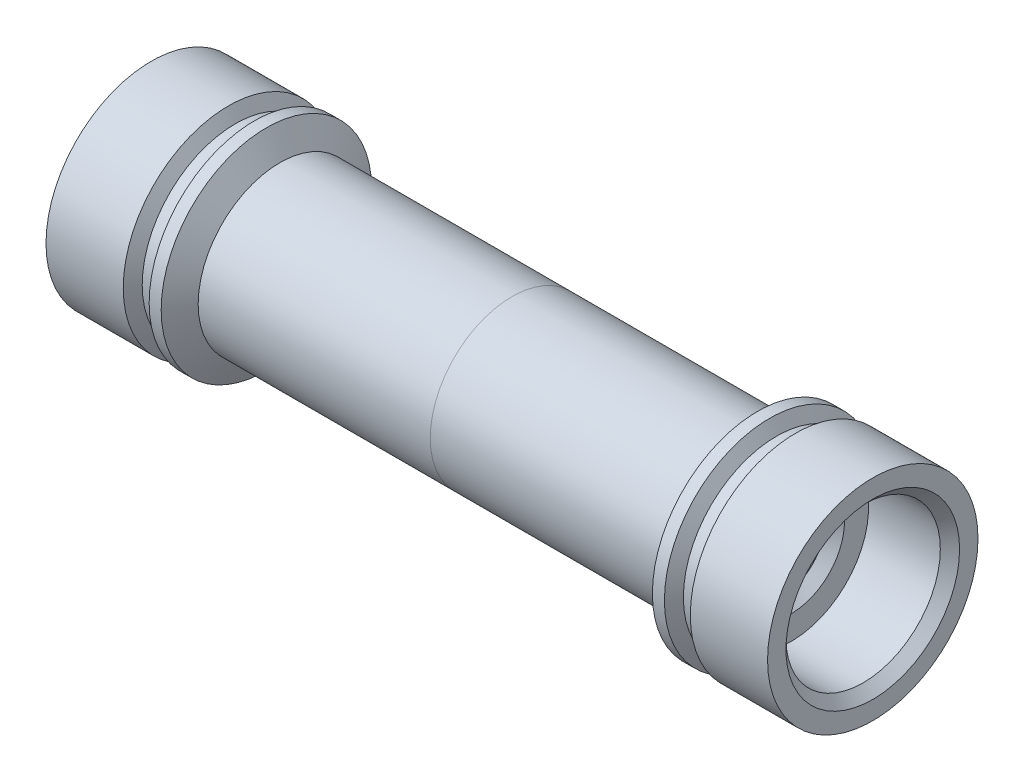
SolidWorks part; units mm, degrees
ref_plane "Front Plane" through (0, 0, 0) normal (0, 0, 1) x (1, 0, 0)
ref_plane "Top Plane" through (0, 0, 0) normal (0, 1, 0) x (1, 0, 0)
ref_plane "Right Plane" through (0, 0, 0) normal (1, 0, 0) x (0, 0, -1)
sketch "Sketch2" plane through (0, 0, 0) normal (0, 0, 1) x (1, 0, 0)
  line L0 (0, 0) -> (0, 28.4375) construction
  line L1 (-19.05, 4.075) -> (-14.75, 4.075) construction
  line L2 (-19.05, 4.075) -> (-19.05, -4.075) construction
  line L3 (-19.05, -4.075) -> (-14.75, -4.075) construction
  line L4 (-14.75, 4.075) -> (-14.75, -4.075) construction
  line L5 (-19.05, 4.075) -> (-14.75, -4.075) construction
  line L6 (-19.05, -4.075) -> (-14.75, 4.075) construction
  line L7 (14.75, 4.5) -> (48.8332, 4.5) construction
  line L8 (14.75, 4.5) -> (14.75, -4.5) construction
  line L9 (14.75, -4.5) -> (48.8332, -4.5) construction
  line L10 (48.8332, 4.5) -> (48.8332, -4.5) construction
  line L11 (14.75, 4.5) -> (48.8332, -4.5) construction
  line L12 (14.75, -4.5) -> (48.8332, 4.5) construction
  line L13 (-19.05, 0) -> (48.8332, 0) construction
  line L14 (-19.05, 5.5562) -> (-14.9716, 5.5562)
  line L21 (-12.2535, 4.318) -> (0, 4.318)
  line L22 (-19.05, 5.5562) -> (-19.05, 4.075)
  line L23 (-19.05, 4.075) -> (-14.75, 4.075)
  line L24 (-14.75, 4.075) -> (-14.75, 0)
  line L25 (-14.75, 0) -> (0, 0)
  line L26 (0, 0) -> (0, 4.318)
  line L27 (-33.5594, -5.5562) -> (-33.5594, 5.5562) construction
  line L28 (-14.9716, 5.5562) -> (-14.605, 4.9212)
  line L29 (-14.605, 4.9212) -> (-13.97, 4.9212)
  line L30 (-19.05, 5.5562) -> (19.05, 5.5562) construction
  line L31 (0, 1.625) -> (-6.5, 1.625)
  line L32 (-6.5, 1.625) -> (-8.125, 0)
  line L33 (-6.5, 1.625) -> (-6.5, -1.625) construction
  line L34 (-6.5, 1.625) -> (6.5, 1.625) construction
  line L35 (-14.75, 1.905) -> (-9.098, 1.905)
  line L36 (-9.098, 1.905) -> (-9.098, 0)
  line L37 (-14.75, 2.805) -> (-14.242, 2.297)
  line L38 (-9.098, 1.905) -> (-22.098, 1.905) construction
  line L39 (-9.098, 1.905) -> (-9.098, -1.905) construction
  line L40 (-9.098, -1.905) -> (-22.098, -1.905) construction
  line L41 (-22.098, 1.905) -> (-22.098, -1.905) construction
  line L42 (-14.242, 2.297) -> (-14.242, 0)
  line L46 (-13.97, 4.9212) -> (-13.6034, 5.5562)
  line L47 (-13.6034, 5.5562) -> (-12.9684, 5.5562)
  line L48 (-12.9684, 5.5562) -> (-12.2535, 4.318)
  line L49 (-14.2875, 4.9212) -> (-14.2875, 6.3987) construction
  line L50 (-14.2875, 6.3987) -> (14.2875, 6.3987) construction
  point P0 (-16.9, 0)
  point P5 (31.7916, 0)
  point P27 (-33.5594, 0)
  point P29 (-6.5, 0)
  point P33 (0, 6.3987)
  point P36 (0, 1.625)
  point P48 (-9.098, 0)
  point P51 (0, 5.5562)
  dimension "D3" = 4.318
  dimension "D4" = 11.1125
  dimension "D5" = 8.15
  dimension "D13" = 45
  dimension "D14" = 13
  dimension "D15" = 3.25
  dimension "D16" = 3.81
  dimension "D17" = 3.048
  dimension "D18" = 1.27
  dimension "D19" = 0.508
  dimension "D20" = 45
  dimension "D21" = 13
  dimension "D11" = 38.1
  dimension "D6" = 60
  dimension "D7" = 0.635
  dimension "D8" = 60
  dimension "D9" = 28.575
  dimension "D10" = 0.635
  dimension "D12" = 0.635
  dimension "D22" = 4.3
revolve "Revolve1" add sketch "Sketch2" angle 360 about L13
chamfer "Chamfer1" distance 0.508 angle 45 1 edges at (-19.05, 0, 4.075)
mirror "Mirror1" about plane through (0, 0, 0) normal (1, 0, 0) of bodies 101
equation "\"D15@Sketch2\"=3mm+.25mm"
equation "\"D22@Sketch2\"=4.3mm"
